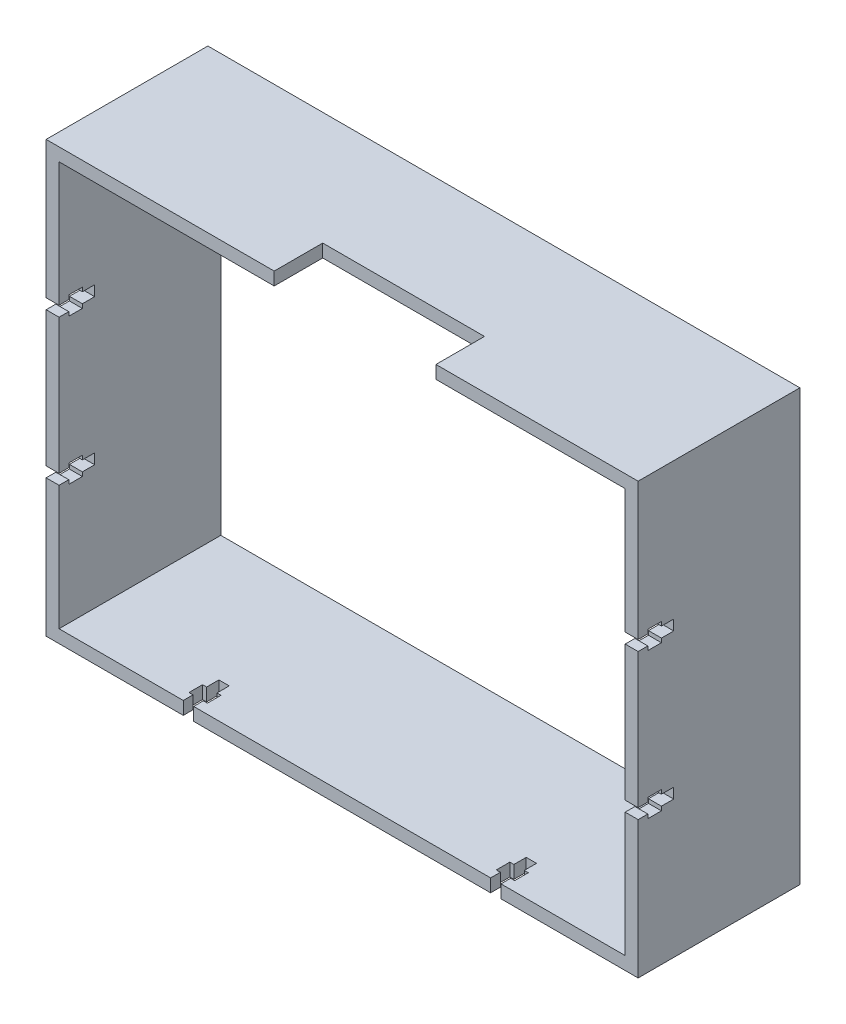
SolidWorks part; units mm, degrees
ref_plane "Plan de face" through (0, 0, 0) normal (0, 0, 1) x (1, 0, 0)
ref_plane "Plan de dessus" through (0, 0, 0) normal (0, 1, 0) x (1, 0, 0)
ref_plane "Plan de droite" through (0, 0, 0) normal (1, 0, 0) x (0, 0, -1)
sketch "Esquisse2" plane through (0, 0, 0) normal (0, 0, 1) x (1, 0, 0)
  line L0 (-85.9962, -62.5) -> (-87.5, -62.5)
  line L2 (87.5, -62.5) -> (87.5, 62.5)
  line L3 (87.5, 62.5) -> (-87.5, 62.5)
  line L4 (-87.5, -62.5) -> (-87.5, 62.5)
  line L5 (87.5, -62.5) -> (-87.5, 62.5) construction
  line L6 (87.5, 62.5) -> (-87.5, -62.5) construction
  line L8 (91.5, -66.5) -> (91.5, 66.5)
  line L9 (91.5, 66.5) -> (-91.5, 66.5)
  line L10 (-91.5, -66.5) -> (-91.5, 66.5)
  line L11 (91.5, -66.5) -> (-91.5, 66.5) construction
  line L12 (91.5, 66.5) -> (-91.5, -66.5) construction
  line L24 (-85.9962, -62.5) -> (87.5, -62.5)
  line L25 (91.5, -66.5) -> (-91.5, -66.5)
  point P0 (0, 0)
  point P6 (0, 0)
  dimension "D1" = 175
  dimension "D2" = 125
  dimension "D3" = 4
  dimension "D4" = 4
extrude "Boss.-Extru.2" add sketch "Esquisse2" along normal blind 50 contours L10 L9 L8 L25 | L4 L3 L2 L24 L0
sketch "Esquisse3" plane through (0, 66.5, 0) normal (0, 1, 0) x (1, 0, 0)
  line L0 (91.5, -50) -> (-91.5, -50) construction
  line L1 (29, -50) -> (-21, -50)
  line L2 (29, -50) -> (29, -35)
  line L3 (29, -35) -> (-21, -35)
  line L4 (-21, -50) -> (-21, -35)
  line L5 (91.5, -50) -> (91.5, 0) construction
  dimension "D1" = 50
  dimension "D2" = 62.5
  dimension "D3" = 15
extrude "Enlèv. mat.-Extru.1" cut sketch "Esquisse3" against normal blind 50
sketch "Esquisse4" plane through (0, 0, 50) normal (0, 0, 1) x (1, 0, 0)
  line L0 (87.5, -62.5) -> (87.5, 62.5) construction
  line L1 (91.5, -66.5) -> (-91.5, -66.5) construction
  line L2 (87.5, -62.5) -> (-87.5, -62.5) construction
  line L3 (0, -86.4168) -> (0, 98.3765) construction
  line L4 (-121.3986, 0) -> (121.7365, 0) construction
  circle A0 centre (89.5, -22.5) radius 1.6
  circle A1 centre (47.5, -64.5) radius 1.6
  circle A2 centre (-89.5, -22.5) radius 1.6
  circle A3 centre (-47.5, -64.5) radius 1.6
  circle A4 centre (-47.5, 64.5) radius 1.6
  circle A5 centre (-89.5, 22.5) radius 1.6
  circle A6 centre (47.5, 64.5) radius 1.6
  circle A7 centre (89.5, 22.5) radius 1.6
  dimension "D1" = 3.2
  dimension "D2" = 3.2
  dimension "D3" = 2
  dimension "D4" = 2
  dimension "D5" = 40
  dimension "D6" = 40
sketch "Esquisse6" plane through (91.5, 0, 0) normal (1, 0, 0) x (0, 0, -1)
  line L8 (-50, 20.9) -> (-47, 20.9)
  line L9 (-50, 20.9) -> (-50, 24.1)
  line L14 (-50, -20.9) -> (-50, -24.1) construction
  line L15 (-50, -24.1) -> (-47, -24.1)
  line L16 (-50, -24.1) -> (-50, -20.9)
  line L17 (-50, -20.9) -> (-47, -20.9)
  line L18 (-39, -24.1) -> (-39, -20.9)
  line L19 (-50, -86.4168) -> (-50, 98.3765) construction
  line L21 (-54, -24.1) -> (-50, -24.1) construction
  line L22 (-47, -20.9) -> (-47, -19.65)
  line L23 (-47, -25.35) -> (-42.8, -25.35)
  line L24 (-47, -25.35) -> (-47, -24.1)
  line L25 (-47, -19.65) -> (-42.8, -19.65)
  line L26 (-42.8, -25.35) -> (-42.8, -24.1)
  line L27 (-42.8, -24.1) -> (-39, -24.1)
  line L28 (-42.8, -20.9) -> (-42.8, -19.65)
  line L29 (-42.8, -20.9) -> (-39, -20.9)
  line L30 (-50, 24.1) -> (-47, 24.1)
  line L31 (-39, 20.9) -> (-39, 24.1)
  line L32 (-47, 24.1) -> (-47, 25.35)
  line L33 (-47, 19.65) -> (-42.8, 19.65)
  line L34 (-47, 19.65) -> (-47, 20.9)
  line L35 (-47, 25.35) -> (-42.8, 25.35)
  line L36 (-42.8, 19.65) -> (-42.8, 20.9)
  line L37 (-42.8, 20.9) -> (-39, 20.9)
  line L38 (-42.8, 24.1) -> (-42.8, 25.35)
  line L39 (-42.8, 24.1) -> (-39, 24.1)
  line L40 (-50, 24.1) -> (-50, 20.9) construction
  line L41 (-50, 24.1) -> (-54, 24.1) construction
  dimension "D2" = 11
  dimension "D3" = 3.2
  dimension "D4" = 5.7
  dimension "D5" = 1.25
  dimension "D6" = 4.2
  dimension "D7" = 3
  dimension "D8" = 0
  dimension "D9" = 0
  dimension "D10" = 11
  dimension "D11" = 3.2
  dimension "D12" = 0
  dimension "D13" = 5.7
  dimension "D14" = 1.25
  dimension "D15" = 4.2
  dimension "D16" = 3
extrude "Enlèv. mat.-Extru.3" cut sketch "Esquisse6" against normal blind 4
sketch "Esquisse7" plane through (-91.5, 0, 0) normal (-1, 0, 0) x (0, 0, 1)
  line L12 (47, 20.9) -> (50, 20.9)
  line L13 (47, 19.65) -> (47, 20.9)
  line L14 (42.8, 19.65) -> (47, 19.65)
  line L15 (42.8, 20.9) -> (42.8, 19.65)
  line L16 (39, 20.9) -> (42.8, 20.9)
  line L17 (39, 24.1) -> (39, 20.9)
  line L18 (42.8, 24.1) -> (39, 24.1)
  line L19 (42.8, 25.35) -> (42.8, 24.1)
  line L20 (47, 25.35) -> (42.8, 25.35)
  line L21 (47, 24.1) -> (47, 25.35)
  line L22 (50, 24.1) -> (47, 24.1)
  line L23 (50, 20.9) -> (50, 24.1)
  line L24 (47, 20.9) -> (50, 20.9)
  line L25 (47, 19.65) -> (47, 20.9)
  line L26 (42.8, 19.65) -> (47, 19.65)
  line L27 (42.8, 20.9) -> (42.8, 19.65)
  line L28 (39, 20.9) -> (42.8, 20.9)
  line L29 (39, 24.1) -> (39, 20.9)
  line L30 (42.8, 24.1) -> (39, 24.1)
  line L31 (42.8, 25.35) -> (42.8, 24.1)
  line L32 (47, 25.35) -> (42.8, 25.35)
  line L33 (47, 24.1) -> (47, 25.35)
  line L34 (50, 24.1) -> (47, 24.1)
  line L35 (50, 20.9) -> (50, 24.1)
  line L36 (47, -24.1) -> (50, -24.1)
  line L37 (50, -24.1) -> (50, -20.9)
  line L38 (50, -20.9) -> (47, -20.9)
  line L39 (47, -20.9) -> (47, -19.65)
  line L40 (47, -19.65) -> (42.8, -19.65)
  line L41 (42.8, -19.65) -> (42.8, -20.9)
  line L42 (42.8, -20.9) -> (39, -20.9)
  line L43 (39, -20.9) -> (39, -24.1)
  line L44 (39, -24.1) -> (42.8, -24.1)
  line L45 (42.8, -24.1) -> (42.8, -25.35)
  line L46 (42.8, -25.35) -> (47, -25.35)
  line L47 (47, -25.35) -> (47, -24.1)
  line L48 (47, -24.1) -> (50, -24.1)
  line L49 (50, -24.1) -> (50, -20.9)
  line L50 (50, -20.9) -> (47, -20.9)
  line L51 (47, -20.9) -> (47, -19.65)
  line L52 (47, -19.65) -> (42.8, -19.65)
  line L53 (42.8, -19.65) -> (42.8, -20.9)
  line L54 (42.8, -20.9) -> (39, -20.9)
  line L55 (39, -20.9) -> (39, -24.1)
  line L56 (39, -24.1) -> (42.8, -24.1)
  line L57 (42.8, -24.1) -> (42.8, -25.35)
  line L58 (42.8, -25.35) -> (47, -25.35)
  line L59 (47, -25.35) -> (47, -24.1)
  dimension "D1" = 0
  dimension "D2" = 0
extrude "Enlèv. mat.-Extru.4" cut sketch "Esquisse7" against normal blind 4
sketch "Esquisse9" plane through (0, -66.5, 0) normal (0, -1, 0) x (1, 0, 0)
  line L0 (-49.1, 50) -> (-45.9, 50)
  line L1 (-49.1, 50) -> (-49.1, 47)
  line L2 (-49.1, 39) -> (-45.9, 39)
  line L3 (-49.1, 42.8) -> (-50.35, 42.8)
  line L4 (-44.65, 42.8) -> (-45.9, 42.8)
  line L5 (-44.65, 42.8) -> (-44.65, 47)
  line L6 (-44.65, 47) -> (-45.9, 47)
  line L7 (-50.35, 42.8) -> (-50.35, 47)
  line L8 (-44.65, 42.8) -> (-50.35, 47) construction
  line L9 (-44.65, 47) -> (-50.35, 42.8) construction
  line L10 (-49.1, 47) -> (-50.35, 47)
  line L11 (-49.1, 42.8) -> (-49.1, 39)
  line L12 (-45.9, 42.8) -> (-45.9, 39)
  line L13 (-45.9, 50) -> (-45.9, 47)
  line L14 (-121.3986, 50) -> (121.7365, 50) construction
  line L15 (-49.1, 54) -> (-49.1, 50) construction
  line L16 (0, 61.3923) -> (0, 17.4924) construction
  line L17 (44.65, 47) -> (50.35, 42.8) construction
  line L18 (44.65, 42.8) -> (50.35, 47) construction
  line L19 (45.9, 50) -> (45.9, 47)
  line L20 (45.9, 42.8) -> (45.9, 39)
  line L21 (49.1, 42.8) -> (49.1, 39)
  line L22 (49.1, 47) -> (50.35, 47)
  line L23 (50.35, 42.8) -> (50.35, 47)
  line L24 (44.65, 47) -> (45.9, 47)
  line L25 (44.65, 42.8) -> (44.65, 47)
  line L26 (44.65, 42.8) -> (45.9, 42.8)
  line L27 (49.1, 42.8) -> (50.35, 42.8)
  line L28 (49.1, 39) -> (45.9, 39)
  line L29 (49.1, 50) -> (49.1, 47)
  line L30 (49.1, 50) -> (45.9, 50)
  point P4 (-47.5, 44.9)
  point P32 (47.5, 44.9)
  dimension "D1" = 3.2
  dimension "D2" = 5.7
  dimension "D3" = 4.2
  dimension "D4" = 3
  dimension "D5" = 1.25
  dimension "D6" = 1.25
  dimension "D7" = 1.25
  dimension "D8" = 3.8
  dimension "D9" = 11
  dimension "D10" = 0
  dimension "D11" = 0
extrude "Enlèv. mat.-Extru.5" cut sketch "Esquisse9" against normal blind 4
